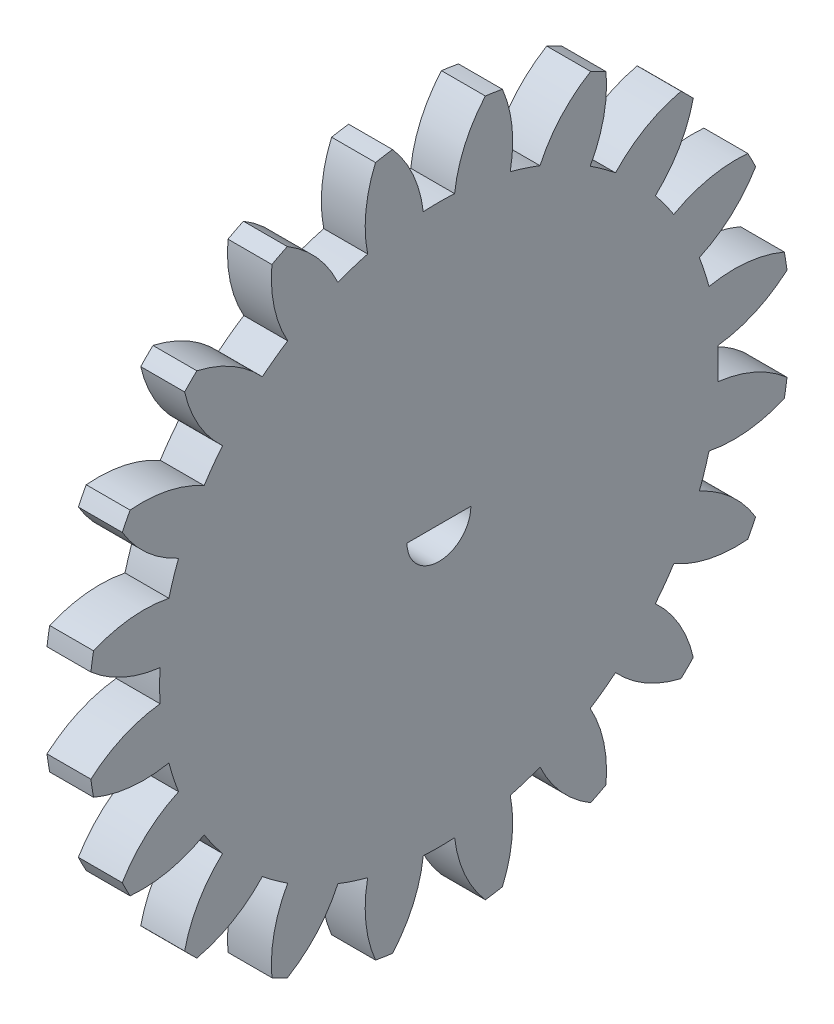
SolidWorks part; units mm, degrees
ref_plane "Plane1" through (0, 0, 0) normal (0, 0, 1) x (1, 0, 0)
ref_plane "Plane2" through (0, 0, 0) normal (0, 1, 0) x (1, 0, 0)
ref_plane "Plane3" through (0, 0, 0) normal (1, 0, 0) x (0, 0, -1)
sketch "HoldingSke" plane through (0, 0, 0) normal (0, 1, 0) x (1, 0, 0)
  line L0 (0, 0) -> (0.2349, -0.0855)
  line L1 (-15, 0) -> (100, 0) construction
  line L2 (0, 0) -> (-2.1039, 2.3779)
  line L3 (0, 0) -> (-11.863, 4.5341)
  line L4 (0, 0) -> (8.1152, 2.9537)
  line L5 (0, 0) -> (-46.8476, -17.4728)
  line L6 (0, 0) -> (-4.5593, -3.0762)
  line L7 (-2.1039, 2.3779) -> (8.6586, 51.2059)
  line L8 (-76.2, 54.61) -> (-76.1, 54.61)
  line L9 (-71.009, 38.7566) -> (-53.1078, 45.2721)
  line L10 (-76.2, 71.12) -> (104.1128, 71.12)
  line L11 (0, 0) -> (-5.5, 0)
  line L12 (-76.2, 101.6) -> (-76.073, 101.6)
  line L13 (24.9733, 27.94) -> (52.9518, 28.4284)
  line L14 (24.9733, 27.94) -> (24.9743, 27.94)
  line L15 (24.9733, 27.94) -> (100.4006, 29.5858)
  line L16 (-63.627, -4) -> (-12.827, -4)
  circle A0 centre (0, 0) radius 0.5
  circle A1 centre (0, 0) radius 34.999
  circle A2 centre (0, 0) radius 37.5
  circle A3 centre (0, 0) radius 0.5
  dimension "MHD" = 69.998
  dimension "Hub_dia" = 75
  dimension "Bore" = 1
  dimension "MBD" = 1
  dimension "Num_teeth" = 20
  dimension "Pitch" = 0.25
  dimension "Overall_len" = 50
  dimension "Show_teeth" = 20
  dimension "Thickness" = 5.5
  dimension "OAL" = 50.0001
  dimension "T_dim" = 0.1
  dimension "Ap" = 20
  dimension "H" = 19.05
  dimension "Pitch_radius" = 180.3128
  dimension "Width" = 5.5
  dimension "Backlash" = 0.127
  dimension "Addendum_fac" = 1
  dimension "Dedendum_fac" = 1.25
  dimension "Clearance_fac" = 0.25
  dimension "Dedendum_add" = 0.001
  dimension "Module" = 4
sketch "BasProSke" plane through (0, 0, 0) normal (0, 1, 0) x (1, 0, 0)
  line L0 (-10, 0) -> (60, 0) construction
  line L1 (0, 0) -> (0, 44)
  line L2 (0, 0) -> (5.5, 0)
  line L3 (5.5, 0) -> (5.5, 44)
  line L4 (5.5, 44) -> (0, 44)
  dimension "Thickness" = 5.5
  dimension "Diameter" = 88
revolve "Base-Revolve" add sketch "BasProSke" angle 360 about L0
sketch "TooCutSke" plane through (0, 0, 0) normal (1, 0, 0) x (0, 0, -1)
  line L1 (0, 0) -> (0, 107) construction
  line L2 (0, 0) -> (-3.3605, 39.8586) construction
  line L3 (0, 0) -> (-12.4815, 78.8048) construction
  line L4 (-3.3605, 39.8586) -> (-6.2407, 39.4024) construction
  arc A0 (1.9617, 34.944) -> (-1.9617, 34.944) centre (0, 0) ccw
  arc A1 (5.8321, 43.6374) -> (-5.8321, 43.6374) centre (0, 0) ccw
  circle A2 centre (0, 0) radius 40 construction
  circle A3 centre (0, 0) radius 37.5877 construction
  arc A4 (-1.9617, 34.944) -> (-5.8321, 43.6374) centre (-17.8525, 33.0775) ccw
  arc A5 (5.8321, 43.6374) -> (1.9617, 34.944) centre (17.8525, 33.0775) ccw
  dimension "Root_dia" = 69.998
  dimension "Overcut_dia" = 88.0508
  dimension "Pitch_dia" = 80
  dimension "Base_dia" = 75.1754
  dimension "Flank_rad" = 16
  dimension "Half_ang" = 9
  dimension "Half_CT" = 2.9161
extrude "ToothCut" cut sketch "TooCutSke" along normal through all
fillet "Breaks" [suppressed] radius 0.08
fillet "RootFillets" [suppressed] radius 1.001
pattern_circular "TeethCuts" count 20 every 18 about axis through (-10, 0, 0) along (1, 0, 0) of "ToothCut", "RootFillets", "Breaks"
sketch "HubNeaOneSke" plane through (0, 0, 0) normal (-1, 0, 0) x (0, 0, 1)
  circle A0 centre (0, 0) radius 34.999
  dimension "Diameter" = 69.998
extrude "HubNearOne" [suppressed] add sketch "HubNeaOneSke" along normal blind 44.5001
sketch "HubNeaBotSke" plane through (0, 0, 0) normal (-1, 0, 0) x (0, 0, 1)
  circle A0 centre (0, 0) radius 34.999
  dimension "Diameter" = 69.998
extrude "HubNearBoth" [suppressed] add sketch "HubNeaBotSke" along normal blind 22.25
ref_plane "FarPln" through (5.5, 0, 0) normal (1, 0, 0) x (0, 0, -1)
sketch "HubFarSke" plane through (5.5, 0, 0) normal (1, 0, 0) x (0, 0, -1)
  circle A0 centre (0, 0) radius 34.999
  dimension "Diameter" = 69.998
extrude "HubFar" [suppressed] add sketch "HubFarSke" along normal blind 22.25
sketch "BorSke" plane through (0, 0, 0) normal (1, 0, 0) x (0, 0, -1)
  circle A0 centre (0, 0) radius 0.5
  dimension "Diameter" = 1
extrude "Bore" cut sketch "BorSke" along normal mid plane 100.0001
sketch "KeySke" plane through (0, 0, 0) normal (1, 0, 0) x (0, 0, -1)
  line L0 (-0.05, 0) -> (-0.05, 0.6)
  line L1 (-0.05, 0.6) -> (0.05, 0.6)
  line L2 (0.05, 0.6) -> (0.05, 0)
  line L3 (0, 0) -> (0, 34) construction
  line L4 (-0.05, 0) -> (0.05, 0)
  dimension "Offset" = 0.6
  dimension "Width" = 0.1
extrude "Keyway" [suppressed] cut sketch "KeySke" along normal mid plane 100.0001
pattern_circular "Keyway2" [suppressed] count 2 every 90 about axis through (-10, 0, 0) along (1, 0, 0)
sketch "Croquis1" plane through (5.5, 0, 0) normal (1, 0, 0) x (0, 0, -1)
  line L0 (-4, 0) -> (4, 0)
  arc A0 (-4, 0) -> (4, 0) centre (0, 0) ccw
  dimension "D1" = 8
extrude "Cortar-Extruir1" cut sketch "Croquis1" against normal blind 5.5
sketch "Croquis2" plane through (5.5, 0, 0) normal (1, 0, 0) x (0, 0, -1)
  line L0 (-0.5, 0) -> (0.5, 0)
  arc A0 (0.5, 0) -> (-0.5, 0) centre (0, 0) ccw
extrude "Saliente-Extruir1" add sketch "Croquis2" against normal blind 5.5
equation "' \"Module@HoldingSke\" = 6.35"
equation "' \"Num_teeth@HoldingSke\" = 12"
equation "' \"Ap@HoldingSke\" =  20"
equation "' \"Ap@HoldingSke\" = 20"
equation "' \"Width@HoldingSke\" = 0.5 * 25.4"
equation "' \"Hub_dia@HoldingSke\"= 1 * 25.4"
equation "' \"Hub_dia@HoldingSke\" = 1 * 25.4"
equation "' \"Overall_len@HoldingSke\" = 1.0 * 25.4"
equation "' \"Bore@HoldingSke\" = 0.75 * 25.4"
equation "' \"T_dim@HoldingSke\" = 0.1 * 25.4"
equation "' \"Width@KeySke\" = 0.25 * 25.4"
equation "' \"Show_teeth@HoldingSke\" = 13"
equation "' \"Backlash@HoldingSke\" = 0.009 * 25.4"
equation "' \"Addendum_fac@HoldingSke\" = 1.0"
equation "' \"Dedendum_fac@HoldingSke\" = 1.25"
equation "' \"Dedendum_add@HoldingSke\" = 0.00005 * 25.4"
equation "' \"Clearance_fac@HoldingSke\" = 0.25"
equation "\"Pitch@HoldingSke\" = 1 / \"Module@HoldingSke\""
equation "\"Overcut_dia@TooCutSke\" = (\"Num_teeth@HoldingSke\" + 2 * \"Addendum_fac@HoldingSke\") / \"Pitch@HoldingSke\" + 0.002 * 25.4"
equation "\"Pitch_dia@TooCutSke\" = \"Num_teeth@HoldingSke\" / \"Pitch@HoldingSke\""
equation "\"Base_dia@TooCutSke\" = \"Num_teeth@HoldingSke\" / \"Pitch@HoldingSke\" * cos((\"Ap@HoldingSke\"  * 3.14159265 / 180))"
equation "\"Root_dia@TooCutSke\" = (\"Num_teeth@HoldingSke\" + 2) / \"Pitch@HoldingSke\" - 2 * (\"Addendum_fac@HoldingSke\" + \"Dedendum_fac@HoldingSke\") / \"Pitch@HoldingSke\" - \"Dedendum_add@HoldingSke\" * 2"
equation "\"Half_ang@TooCutSke\" = 180 / \"Num_teeth@HoldingSke\""
equation "\"Half_CT@TooCutSke\" = \"Num_teeth@HoldingSke\" / \"Pitch@HoldingSke\" * sin((3.14159265 / 2 / \"Num_teeth@HoldingSke\")) / 2 - 7 * \"Backlash@HoldingSke\" / 4"
equation "\"Flank_rad@TooCutSke\" = \"Num_teeth@HoldingSke\" / \"Pitch@HoldingSke\" / 5"
equation "\"Radius@RootFillets\" = \"Clearance_fac@HoldingSke\" / \"Pitch@HoldingSke\" + \"Dedendum_add@HoldingSke\""
equation "\"Break_rad@Breaks\" = 0.02 / \"Pitch@HoldingSke\""
equation "\"Thickness@HoldingSke\" = \"Width@HoldingSke\""
equation "\"OAL@HoldingSke\" = \"Thickness@HoldingSke\""
equation "\"MHD@HoldingSke\" = (\"Num_teeth@HoldingSke\" + 2) / \"Pitch@HoldingSke\" - 2 * (\"Addendum_fac@HoldingSke\" + \"Dedendum_fac@HoldingSke\")  / \"Pitch@HoldingSke\" - \"Dedendum_add@HoldingSke\" * 2"
equation "\"MBD@HoldingSke\" = (\"Num_teeth@HoldingSke\" + 2) / \"Pitch@HoldingSke\" - 2 * (\"Addendum_fac@HoldingSke\" + \"Dedendum_fac@HoldingSke\")  / \"Pitch@HoldingSke\" - \"Dedendum_add@HoldingSke\" * 2 - 0.002 * 25.4"
equation "\"MHD@HoldingSke\" = ((sgn( \"MHD@HoldingSke\" - \"Hub_dia@HoldingSke\" )-1)*( \"MHD@HoldingSke\" - \"Hub_dia@HoldingSke\" ))/-2+ \"Hub_dia@HoldingSke\""
equation "\"MBD@HoldingSke\" = ((sgn( \"MBD@HoldingSke\" - \"Bore@HoldingSke\" )-1)*( \"MBD@HoldingSke\" - \"Bore@HoldingSke\" ))/-2+ \"Bore@HoldingSke\""
equation "\"OAL@HoldingSke\" = ((sgn( \"OAL@HoldingSke\" - \"Overall_len@HoldingSke\" )+1)*( \"OAL@HoldingSke\" - \"Overall_len@HoldingSke\" ))/2 + \"Overall_len@HoldingSke\" + 0.000002 * 25.4"
equation "\"Num_teeth@TeethCuts\" = int( \"Show_teeth@HoldingSke\" ) + 1"
equation "\"Num_teeth@TeethCuts\" = ((sgn( \"Num_teeth@TeethCuts\" - \"Num_teeth@HoldingSke\" )-1)*( \"Num_teeth@TeethCuts\" - \"Num_teeth@HoldingSke\" ))/-2+ \"Num_teeth@HoldingSke\""
equation "\"Num_teeth@TeethCuts\" = ((sgn( \"Num_teeth@TeethCuts\" - 2.0)+1)*( \"Num_teeth@TeethCuts\" - 2.0))/2 +2.0"
equation "\"Angle@TeethCuts\" = 360.0 / \"Num_teeth@HoldingSke\""
equation "\"Diameter@BasProSke\" = (\"Num_teeth@HoldingSke\" + 2 * \"Addendum_fac@HoldingSke\") / \"Pitch@HoldingSke\""
equation "\"Thickness@BasProSke\"  = \"Thickness@HoldingSke\""
equation "' \"Fillet_rad@BasProSke\" =  \"Thickness@HoldingSke\" * 0.05"
equation "' \"Fillet_rad@BasProSke\" = \"Thickness@HoldingSke\" * 0.05"
equation "\"MHD@HoldingSke\" = ((sgn( \"MHD@HoldingSke\" - \"Root_dia@TooCutSke\" )-1)*( \"MHD@HoldingSke\" - \"Root_dia@TooCutSke\" ))/-2+ \"Root_dia@TooCutSke\""
equation "\"Diameter@HubNeaOneSke\" = \"MHD@HoldingSke\""
equation "\"Length@HubNearOne\" = \"OAL@HoldingSke\" - \"Thickness@BasProSke\""
equation "\"Diameter@HubNeaBotSke\" = \"MHD@HoldingSke\""
equation "\"Length@HubNearBoth\" = ( \"OAL@HoldingSke\" - \"Thickness@BasProSke\" ) / 2.0"
equation "\"Thickness@FarPln\" = \"Thickness@BasProSke\""
equation "\"Diameter@HubFarSke\" = \"MHD@HoldingSke\""
equation "\"Length@HubFar\" = ( \"OAL@HoldingSke\" - \"Thickness@BasProSke\" ) / 2.0"
equation "\"Diameter@BorSke\" = \"MBD@HoldingSke\""
equation "\"D1@Bore\" = \"OAL@HoldingSke\" * 2.0"
equation "\"D1@Keyway\" = \"OAL@HoldingSke\" * 2.0"
equation "\"Offset@KeySke\" = \"T_dim@HoldingSke\" + \"MBD@HoldingSke\" / 2.0"
